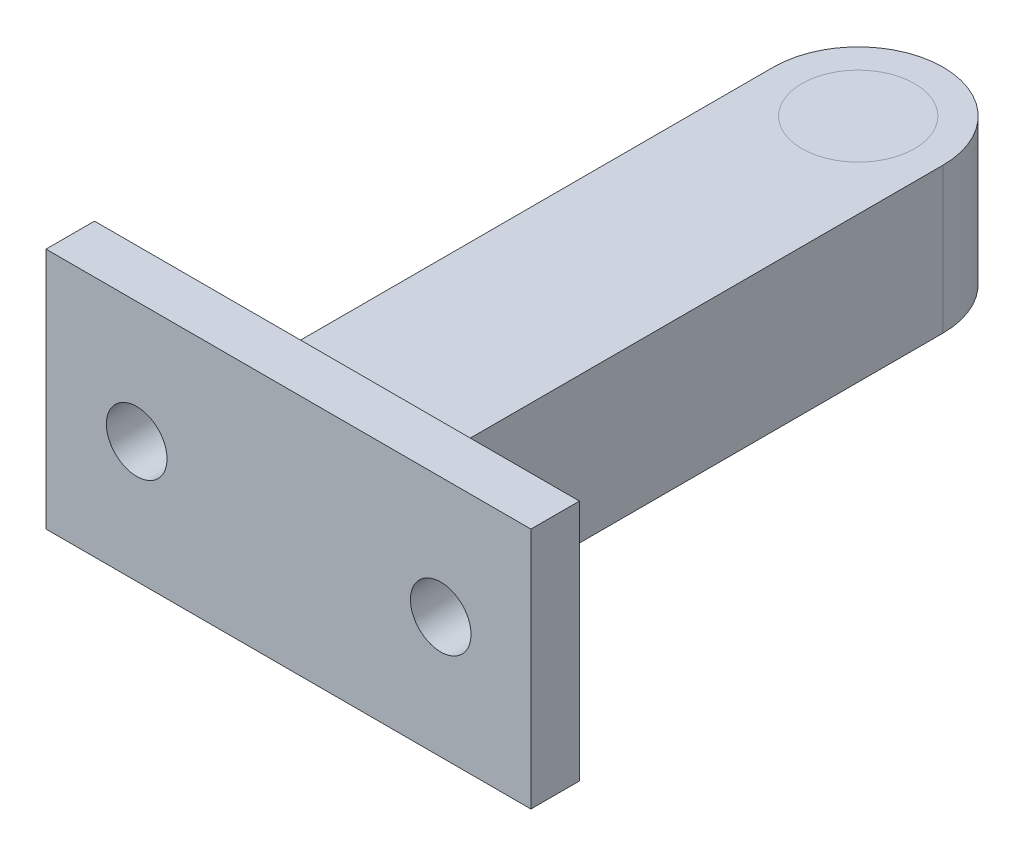
SolidWorks part; units mm, degrees
ref_plane "Front Plane" through (0, 0, 0) normal (0, 0, 1) x (1, 0, 0)
ref_plane "Top Plane" through (0, 0, 0) normal (0, 1, 0) x (1, 0, 0)
ref_plane "Right Plane" through (0, 0, 0) normal (1, 0, 0) x (0, 0, -1)
sketch "Sketch1" plane through (0, 0, 0) normal (0, 1, 0) x (1, 0, 0)
  line L1 (-3.5, 0) -> (3.5, 0)
  line L2 (-3.5, 0) -> (-3.5, -21.5)
  line L3 (-3.5, -21.5) -> (3.5, -21.5)
  line L4 (3.5, 0) -> (3.5, -21.5)
  circle A0 centre (0, 0) radius 3.5
  circle A1 centre (0, 0) radius 2.325
  dimension "D1" = 4.65
  dimension "D2" = 7
  dimension "D3" = 21.5
extrude "Boss-Extrude1" add sketch "Sketch1" along normal blind 6 contours A0 L2 L3 L4 | A1 L1 A0 | A1 L1 A0
sketch "Sketch2" plane through (0, 0, 21.5) normal (0, 0, 1) x (1, 0, 0)
  line L1 (-10, 8) -> (10, 8)
  line L2 (-10, 8) -> (-10, -2)
  line L3 (-10, -2) -> (10, -2)
  line L4 (10, 8) -> (10, -2)
  line L6 (-3.5, 0) -> (3.5, 6) construction
  line L7 (-10, 8) -> (10, -2) construction
  point P4 (0, 3)
  point P5 (0, 3)
  dimension "D1" = 20
  dimension "D2" = 10
extrude "Boss-Extrude2" add sketch "Sketch2" along normal blind 2
hole_wizard "Tap Drill for M3x0.5 Tap1" positions "Sketch3" profile "Sketch4" hole size "M3x0.5" standard "ANSI Metric"
sketch "Sketch3" plane through (0, 0, 21.5) normal (0, 0, -1) x (-1, 0, 0)
  line L0 (-10, 3) -> (10, 3) construction
  line L1 (-10, -2) -> (-10, 8) construction
  line L2 (10, 8) -> (10, -2) construction
  line L3 (-10, 3) -> (10, 3) construction
  line L4 (-10, -2) -> (-10, 8) construction
  line L5 (10, 8) -> (10, -2) construction
  line L24 (0, -2) -> (0, 8) construction
  line L25 (10, -2) -> (-10, -2) construction
  line L26 (-10, 8) -> (10, 8) construction
  line L29 (0, -2) -> (0, 8) construction
  line L30 (10, -2) -> (-10, -2) construction
  line L31 (-10, 8) -> (10, 8) construction
  line L32 (-10, -2) -> (0, 8) construction
  line L33 (0, 8) -> (10, -2) construction
  line L34 (10, -2) -> (-10, -2) construction
  line L35 (10, 8) -> (10, -2) construction
  point P81 (0, 3)
  point P83 (5.25, 3)
  point P94 (-6.2811, 3)
  point P96 (6.2577, 3)
sketch "Sketch4" plane through (-6.2577, 3, 21.5) normal (1, 0, 0) x (0, 1, 0)
  line L0 (0, 0) -> (0, 2)
  line L1 (0, 2) -> (1.25, 2)
  line L2 (1.25, 2) -> (1.25, 0)
  line L5 (1.25, 0) -> (0, 0)
  line L11 (0, -6.35) -> (0, 107.95) construction
  dimension "Thru Hole Dia." = 2.5
  dimension "Thru Hole Depth" = 2
sketch "Sketch5" plane through (0, 6, 0) normal (0, 1, 0) x (1, 0, 0)
  circle A0 centre (0, 0) radius 2.325
  circle A1 centre (0, 0) radius 2.325 construction
extrude "Boss-Extrude3" add sketch "Sketch5" against normal blind 0.5 separate body
